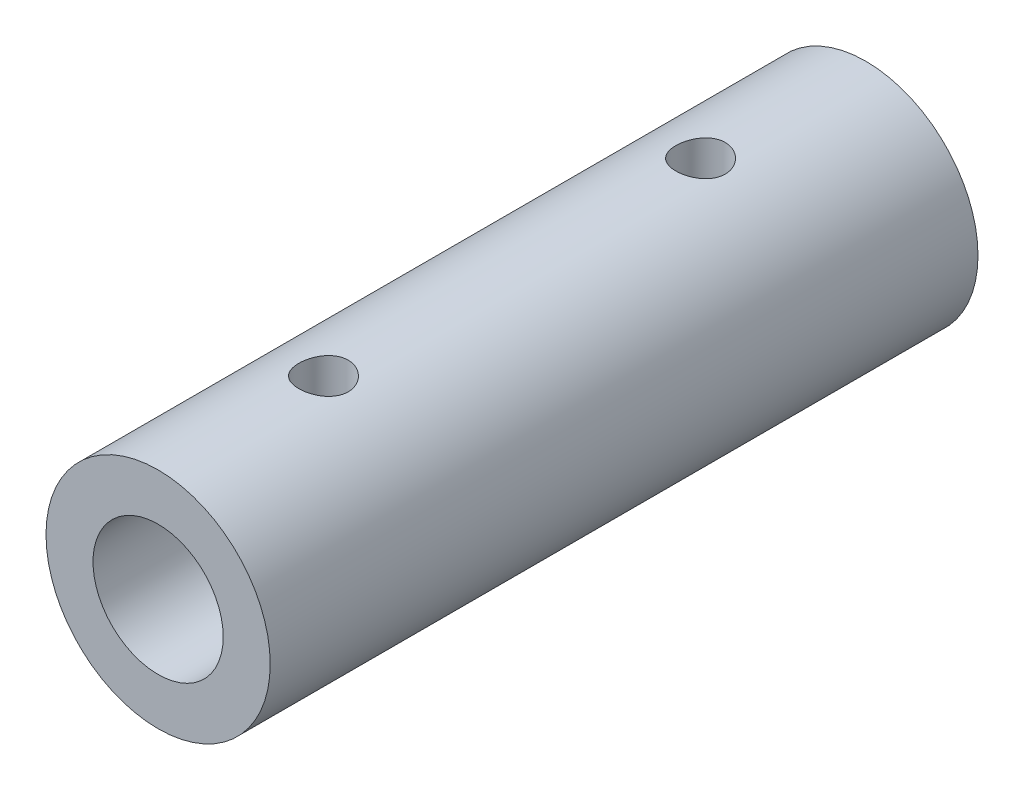
SolidWorks part; units mm, degrees
material "AISI 1020"
ref_plane "Front Plane" through (0, 0, 0) normal (0, 0, 1) x (1, 0, 0)
ref_plane "Top Plane" through (0, 0, 0) normal (0, 1, 0) x (1, 0, 0)
ref_plane "Right Plane" through (0, 0, 0) normal (1, 0, 0) x (0, 0, -1)
sketch "Sketch1" plane through (0, 0, 0) normal (0, 0, 1) x (1, 0, 0)
  circle A0 centre (0, 0) radius 8.61
  circle A1 centre (0, 0) radius 5
  dimension "D1" = 10
  dimension "D2" = 17.22
extrude "Boss-Extrude1" add sketch "Sketch1" along normal blind 54.356
hole_wizard "#10-24 Tapped Hole1" positions "Sketch3" profile "Sketch2" tap size "#10-24" standard "ANSI Inch"
sketch "Sketch3" plane through (0, 0, 0) normal (0, 1, 0) x (1, 0, 0)
  line L0 (-8.61, -54.356) -> (8.61, -54.356) construction
  point P0 (0, -12.7)
  point P2 (0, -41.656)
  dimension "D1" = 12.7
  dimension "D2" = 12.7
sketch "Sketch2" plane through (0, 0, 12.7) normal (1, 0, 0) x (0, 0, -1)
  line L0 (0, 0) -> (0, 8.61)
  line L1 (0, 8.61) -> (1.8986, 8.61)
  line L2 (1.8986, 8.61) -> (1.8986, 0)
  line L5 (1.8986, 0) -> (0, 0)
  line L11 (0, -6.35) -> (0, 107.95) construction
  dimension "Thru Tap Drill Dia." = 3.7973
  dimension "Thru Tap Drill Depth" = 8.61
hole_wizard "#10 (0.1935) Diameter Hole3" positions "Sketch7" profile "Sketch8" hole size "#10" standard "ANSI Inch"
sketch "Sketch7" plane through (0, 0, 0) normal (0, 1, 0) x (1, 0, 0)
  point P0 (0, -41.656)
sketch "Sketch8" plane through (0, 0, 41.656) normal (1, 0, 0) x (0, 0, 1)
  line L0 (0, 0) -> (0, 8.61)
  line L1 (0, 8.61) -> (2.4574, 8.61)
  line L2 (2.4574, 8.61) -> (2.4574, 0)
  line L5 (2.4574, 0) -> (0, 0)
  line L11 (0, -6.35) -> (0, 107.95) construction
  dimension "Thru Hole Dia." = 4.9149
  dimension "Thru Hole Depth" = 8.61
equation "\"Router\" = 8.61mm"
equation "\"Rinnner\"= 5mm"
equation "\"Totallength\"= 2.14in"
equation "\"D1@Sketch1\"=\"Rinnner\"*2"
equation "\"D2@Sketch1\"=\"Router\"*2"
equation "\"D1@Boss-Extrude1\"=\"Totallength\""
equation "\"D2@Sketch3\"=\"D1@Sketch3\""
